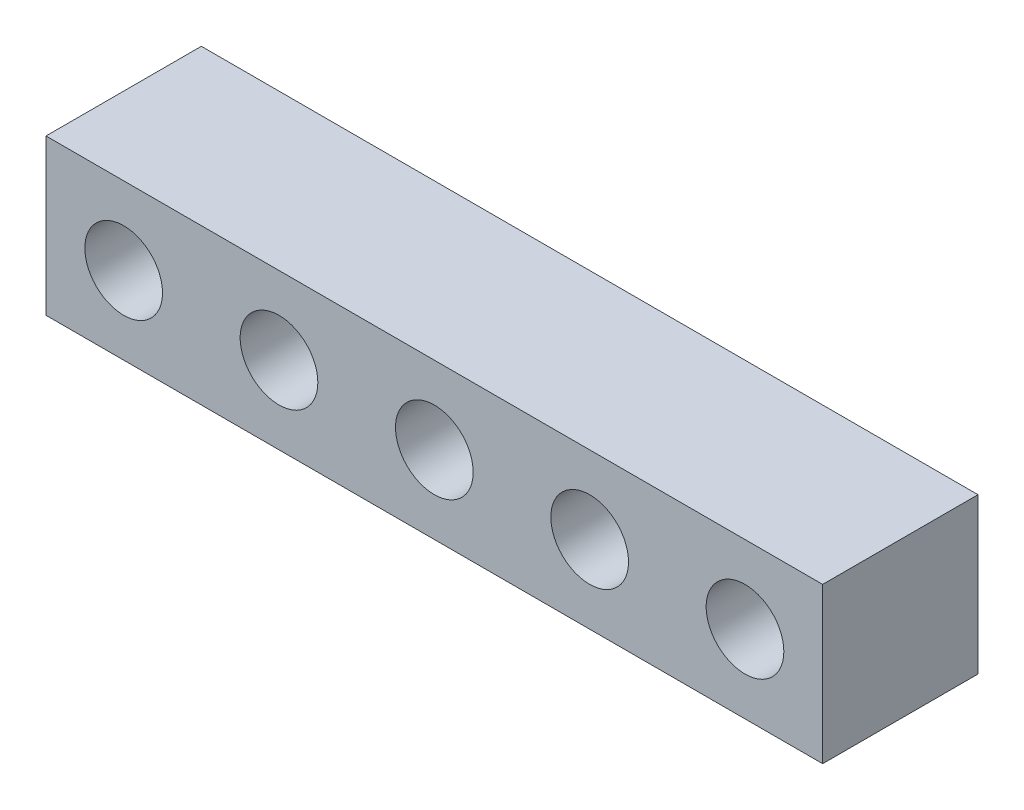
SolidWorks part; units mm, degrees
ref_plane "Plan de face" through (0, 0, 0) normal (0, 0, 1) x (1, 0, 0)
ref_plane "Plan de dessus" through (0, 0, 0) normal (0, 1, 0) x (1, 0, 0)
ref_plane "Plan de droite" through (0, 0, 0) normal (1, 0, 0) x (0, 0, -1)
sketch "Esquisse1" plane through (0, 0, 0) normal (0, 0, 1) x (1, 0, 0)
  line L1 (0, 0) -> (50, 0)
  line L2 (0, 0) -> (0, 10)
  line L3 (0, 10) -> (50, 10)
  line L4 (50, 0) -> (50, 10)
  dimension "D1" = 50
  dimension "D2" = 10
extrude "Boss.-Extru.1" add sketch "Esquisse1" along normal blind 10
sketch "Esquisse2" plane through (0, 0, 10) normal (0, 0, 1) x (1, 0, 0)
  line L0 (0, 10) -> (0, 0) construction
  line L1 (0, 0) -> (50, 0) construction
  circle A0 centre (5, 5) radius 2.5
  circle A1 centre (15, 5) radius 2.5
  circle A2 centre (25, 5) radius 2.5
  circle A3 centre (35, 5) radius 2.5
  circle A4 centre (45, 5) radius 2.5
  dimension "D3" = 5
  dimension "D1" = 5
  dimension "D2" = 5
  dimension "D5" = 10
  dimension "D4" = 5
extrude "Enlèv. mat.-Extru.1" cut sketch "Esquisse2" against normal up to next
